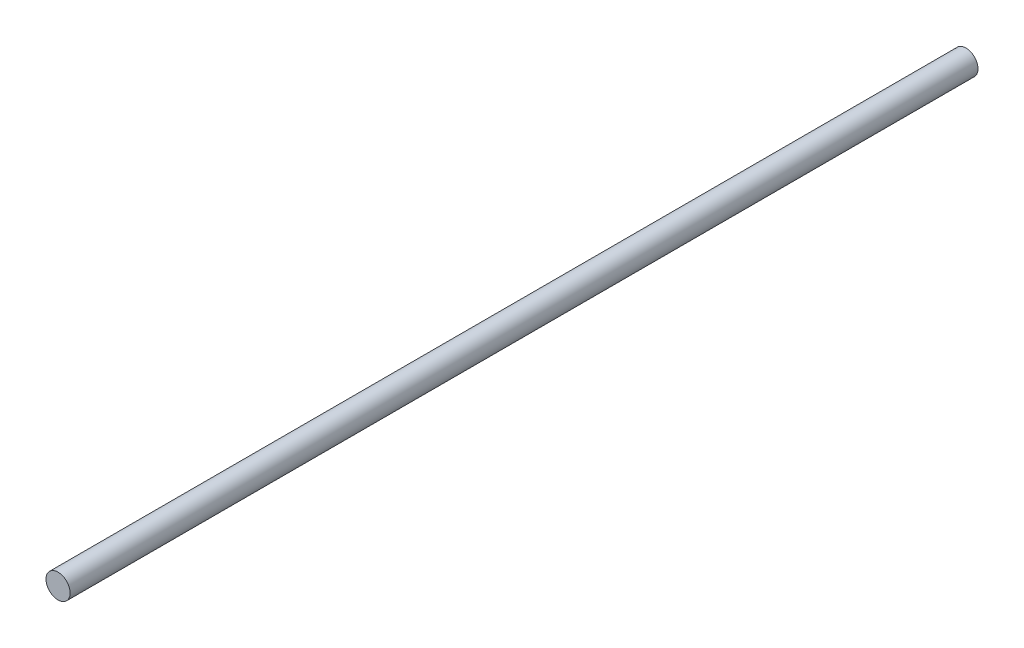
SolidWorks part; units mm, degrees
ref_plane "Front Plane" through (0, 0, 0) normal (0, 0, 1) x (1, 0, 0)
ref_plane "Top Plane" through (0, 0, 0) normal (0, 1, 0) x (1, 0, 0)
ref_plane "Right Plane" through (0, 0, 0) normal (1, 0, 0) x (0, 0, -1)
sketch "Sketch1" plane through (0, 0, 0) normal (0, 0, 1) x (1, 0, 0)
  circle A0 centre (0, 0) radius 1.25
  dimension "D1" = 2.5
extrude "Boss-Extrude1" add sketch "Sketch1" against normal blind 94
